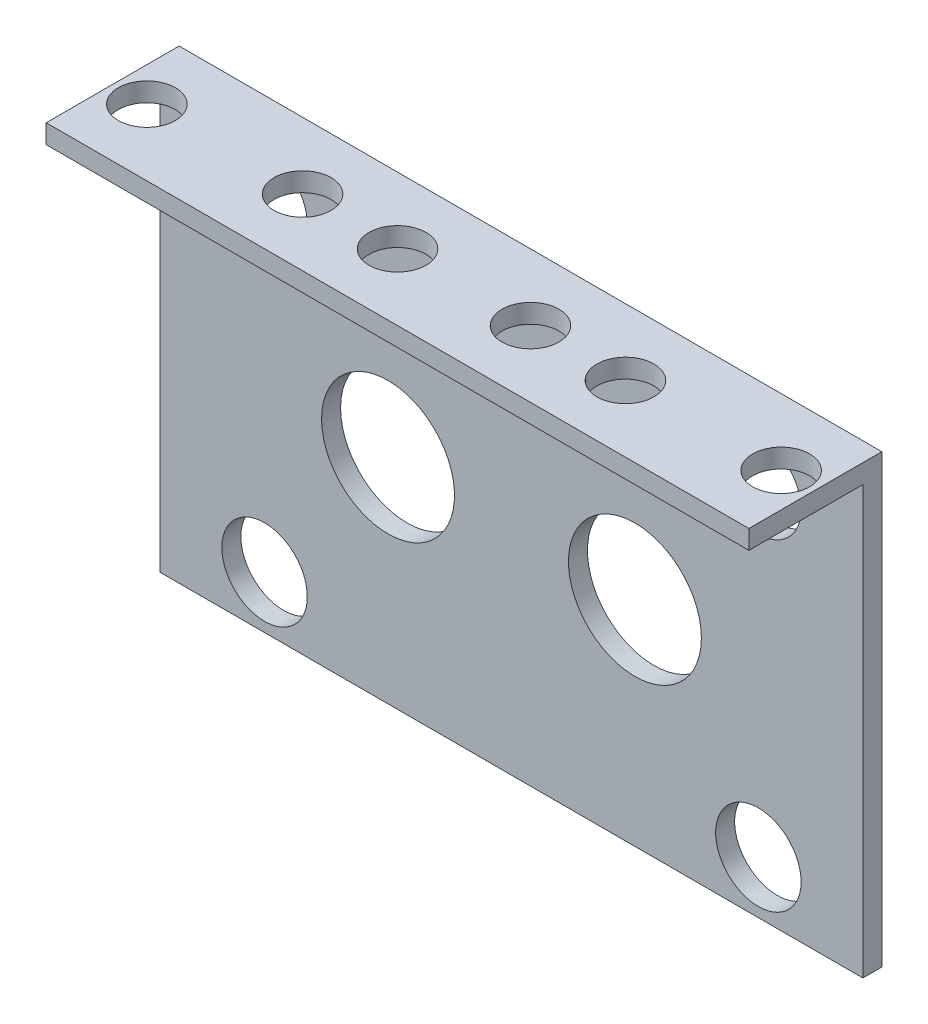
SolidWorks part; units mm, degrees
ref_plane "Plano frontal" through (0, 0, 0) normal (0, 0, 1) x (1, 0, 0)
ref_plane "Plano superior" through (0, 0, 0) normal (0, 1, 0) x (1, 0, 0)
ref_plane "Plano direito" through (0, 0, 0) normal (1, 0, 0) x (0, 0, -1)
sketch "Esboço1" plane through (0, 0, 0) normal (0, 0, 1) x (1, 0, 0)
  line L1 (0, 0) -> (37, 0)
  line L2 (0, 0) -> (0, 22.5)
  line L3 (0, 22.5) -> (37, 22.5)
  line L4 (37, 0) -> (37, 22.5)
  dimension "D1" = 37
  dimension "D2" = 22.5
extrude "Ressalto-extrusão1" add sketch "Esboço1" along normal blind 1
sketch "Esboço2" plane through (0, 0, 1) normal (0, 0, 1) x (1, 0, 0)
  line L0 (37, 22.5) -> (0, 22.5) construction
  line L1 (0, 11.25) -> (37, 11.25) construction
  line L2 (0, 22.5) -> (0, 0) construction
  line L3 (37, 0) -> (37, 22.5) construction
  line L4 (18.5, 22.5) -> (18.5, 0) construction
  line L5 (0, 0) -> (37, 0) construction
  circle A0 centre (5.5, 19.74) radius 2.25
  circle A1 centre (25, 11.25) radius 3.5
  circle A2 centre (5.5, 2.76) radius 2.25
  circle A3 centre (12, 11.25) radius 3.5
  circle A4 centre (31.5, 2.76) radius 2.25
  circle A5 centre (31.5, 19.74) radius 2.25
  dimension "D1" = 4.5
  dimension "D2" = 7
  dimension "D3" = 2.76
  dimension "D4" = 12
  dimension "D5" = 5.5
extrude "Corte-extrusão1" cut sketch "Esboço2" against normal blind 1
sketch "Esboço3" plane through (0, 22.5, 0) normal (0, 1, 0) x (1, 0, 0)
  line L0 (37, -1) -> (37, 0) construction
  line L1 (0, 0) -> (37, 0)
  line L2 (0, 0) -> (0, -7)
  line L3 (0, -7) -> (37, -7)
  line L4 (37, 0) -> (37, -7)
  dimension "D1" = 7
extrude "Ressalto-extrusão2" add sketch "Esboço3" along normal blind 1
sketch "Esboço4" plane through (0, 0, 7) normal (0, 0, 1) x (1, 0, 0)
  line L0 (5.5, 19.74) -> (5.5, 23.5) construction
  line L1 (0, 23.5) -> (37, 23.5) construction
  line L2 (31.5, 19.74) -> (31.5, 23.5) construction
  line L3 (12, 11.25) -> (12, 23.5) construction
  line L4 (25, 11.25) -> (25, 23.5) construction
sketch "Esboço5" plane through (0, 23.5, 0) normal (0, 1, 0) x (1, 0, 0)
  line L0 (37, 0) -> (0, 0) construction
  line L1 (0, 0) -> (0, -7) construction
  line L2 (37, -7) -> (37, 0) construction
  circle A0 centre (1.8, -3.5) radius 1.5
  circle A1 centre (10, -3.5) radius 1.5
  circle A2 centre (15, -3.5) radius 1.5
  circle A3 centre (22, -3.5) radius 1.5
  circle A4 centre (27, -3.5) radius 1.5
  circle A5 centre (35.2, -3.5) radius 1.5
  dimension "D1" = 3
  dimension "D2" = 3.5
  dimension "D3" = 1.8
  dimension "D4" = 10
  dimension "D5" = 15
  dimension "D6" = 15
  dimension "D7" = 10
  dimension "D8" = 1.8
extrude "Corte-extrusão2" cut sketch "Esboço5" against normal blind 1
